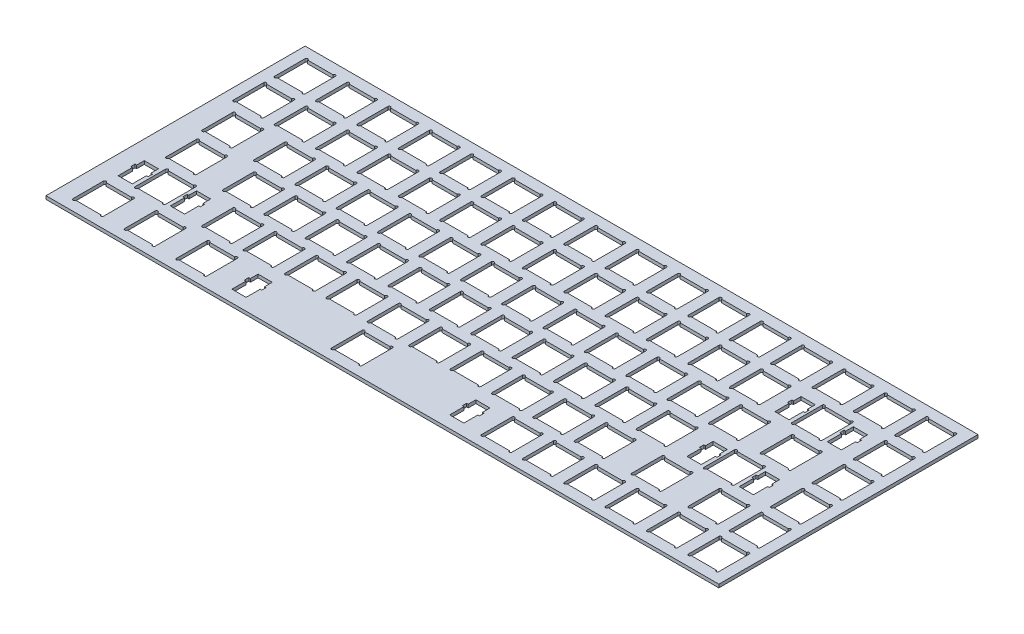
SolidWorks part; units mm, degrees
ref_plane "Спереди" through (0, 0, 0) normal (0, 0, 1) x (1, 0, 0)
ref_plane "Сверху" through (0, 0, 0) normal (0, 1, 0) x (1, 0, 0)
ref_plane "Справа" through (0, 0, 0) normal (1, 0, 0) x (0, 0, -1)
sketch "Эскиз1" plane through (0, 0, 0) normal (0, 1, 0) x (1, 0, 0)
  line L0 (13.2, -7) -> (24.8, -7)
  line L1 (-7, 7) -> (-7, -7)
  line L2 (-5.8, -7) -> (5.8, -7)
  line L3 (7, -7) -> (7, 7)
  line L4 (5.8, 7) -> (-5.8, 7)
  line L5 (12, 7) -> (12, -7)
  line L6 (24.8, 7) -> (13.2, 7)
  line L7 (26, -7) -> (26, 7)
  line L8 (32.2, -7) -> (43.8, -7)
  line L9 (31, 7) -> (31, -7)
  line L10 (43.8, 7) -> (32.2, 7)
  line L11 (45, -7) -> (45, 7)
  line L12 (51.2, -7) -> (62.8, -7)
  line L13 (50, 7) -> (50, -7)
  line L14 (62.8, 7) -> (51.2, 7)
  line L15 (64, -7) -> (64, 7)
  line L16 (70.2, -7) -> (81.8, -7)
  line L17 (69, 7) -> (69, -7)
  line L18 (81.8, 7) -> (70.2, 7)
  line L19 (83, -7) -> (83, 7)
  line L20 (89.2, -7) -> (100.8, -7)
  line L21 (88, 7) -> (88, -7)
  line L22 (100.8, 7) -> (89.2, 7)
  line L23 (102, -7) -> (102, 7)
  line L24 (108.2, -7) -> (119.8, -7)
  line L25 (107, 7) -> (107, -7)
  line L26 (119.8, 7) -> (108.2, 7)
  line L27 (121, -7) -> (121, 7)
  line L28 (127.2, -7) -> (138.8, -7)
  line L29 (126, 7) -> (126, -7)
  line L30 (138.8, 7) -> (127.2, 7)
  line L31 (140, -7) -> (140, 7)
  line L32 (146.2, -7) -> (157.8, -7)
  line L33 (145, 7) -> (145, -7)
  line L34 (157.8, 7) -> (146.2, 7)
  line L35 (159, -7) -> (159, 7)
  line L36 (165.2, -7) -> (176.8, -7)
  line L37 (164, 7) -> (164, -7)
  line L38 (176.8, 7) -> (165.2, 7)
  line L39 (178, -7) -> (178, 7)
  line L40 (184.2, -7) -> (195.8, -7)
  line L41 (183, 7) -> (183, -7)
  line L42 (195.8, 7) -> (184.2, 7)
  line L43 (197, -7) -> (197, 7)
  line L44 (203.2, -7) -> (214.8, -7)
  line L45 (202, 7) -> (202, -7)
  line L46 (214.8, 7) -> (203.2, 7)
  line L47 (216, -7) -> (216, 7)
  line L48 (222.2, -7) -> (233.8, -7)
  line L49 (221, 7) -> (221, -7)
  line L50 (233.8, 7) -> (222.2, 7)
  line L51 (235, -7) -> (235, 7)
  line L52 (241.2, -7) -> (252.8, -7)
  line L53 (240, 7) -> (240, -7)
  line L54 (252.8, 7) -> (241.2, 7)
  line L55 (254, -7) -> (254, 7)
  line L56 (260.2, -7) -> (271.8, -7)
  line L57 (259, 7) -> (259, -7)
  line L58 (271.8, 7) -> (260.2, 7)
  line L59 (273, -7) -> (273, 7)
  line L60 (279.2, -7) -> (290.8, -7)
  line L61 (278, 7) -> (278, -7)
  line L62 (290.8, 7) -> (279.2, 7)
  line L63 (292, -7) -> (292, 7)
  line L64 (279.2, -26) -> (290.8, -26)
  line L65 (278, -12) -> (278, -26)
  line L66 (290.8, -12) -> (279.2, -12)
  line L67 (292, -26) -> (292, -12)
  line L68 (279.2, -45) -> (290.8, -45)
  line L69 (278, -31) -> (278, -45)
  line L70 (290.8, -31) -> (279.2, -31)
  line L71 (292, -45) -> (292, -31)
  line L72 (279.2, -64) -> (290.8, -64)
  line L73 (278, -50) -> (278, -64)
  line L74 (290.8, -50) -> (279.2, -50)
  line L75 (292, -64) -> (292, -50)
  line L76 (279.2, -83) -> (290.8, -83)
  line L77 (278, -69) -> (278, -83)
  line L78 (290.8, -69) -> (279.2, -69)
  line L79 (292, -83) -> (292, -69)
  line L80 (279.2, -102) -> (290.8, -102)
  line L81 (278, -88) -> (278, -102)
  line L82 (290.8, -88) -> (279.2, -88)
  line L83 (292, -102) -> (292, -88)
  line L84 (-7, -12) -> (-7, -26)
  line L85 (-5.8, -26) -> (5.8, -26)
  line L86 (7, -26) -> (7, -12)
  line L87 (5.8, -12) -> (-5.8, -12)
  line L88 (12, -12) -> (12, -26)
  line L89 (13.2, -26) -> (24.8, -26)
  line L90 (26, -26) -> (26, -12)
  line L91 (24.8, -12) -> (13.2, -12)
  line L92 (31, -12) -> (31, -26)
  line L93 (32.2, -26) -> (43.8, -26)
  line L94 (45, -26) -> (45, -12)
  line L95 (43.8, -12) -> (32.2, -12)
  line L96 (50, -12) -> (50, -26)
  line L97 (51.2, -26) -> (62.8, -26)
  line L98 (64, -26) -> (64, -12)
  line L99 (62.8, -12) -> (51.2, -12)
  line L100 (69, -12) -> (69, -26)
  line L101 (70.2, -26) -> (81.8, -26)
  line L102 (83, -26) -> (83, -12)
  line L103 (81.8, -12) -> (70.2, -12)
  line L104 (88, -12) -> (88, -26)
  line L105 (89.2, -26) -> (100.8, -26)
  line L106 (102, -26) -> (102, -12)
  line L107 (100.8, -12) -> (89.2, -12)
  line L108 (107, -12) -> (107, -26)
  line L109 (108.2, -26) -> (119.8, -26)
  line L110 (121, -26) -> (121, -12)
  line L111 (119.8, -12) -> (108.2, -12)
  line L112 (126, -12) -> (126, -26)
  line L113 (127.2, -26) -> (138.8, -26)
  line L114 (140, -26) -> (140, -12)
  line L115 (138.8, -12) -> (127.2, -12)
  line L116 (145, -12) -> (145, -26)
  line L117 (146.2, -26) -> (157.8, -26)
  line L118 (159, -26) -> (159, -12)
  line L119 (157.8, -12) -> (146.2, -12)
  line L120 (164, -12) -> (164, -26)
  line L121 (165.2, -26) -> (176.8, -26)
  line L122 (178, -26) -> (178, -12)
  line L123 (176.8, -12) -> (165.2, -12)
  line L124 (183, -12) -> (183, -26)
  line L125 (184.2, -26) -> (195.8, -26)
  line L126 (197, -26) -> (197, -12)
  line L127 (195.8, -12) -> (184.2, -12)
  line L128 (202, -12) -> (202, -26)
  line L129 (203.2, -26) -> (214.8, -26)
  line L130 (216, -26) -> (216, -12)
  line L131 (214.8, -12) -> (203.2, -12)
  line L132 (221, -12) -> (221, -26)
  line L133 (222.2, -26) -> (233.8, -26)
  line L134 (235, -26) -> (235, -12)
  line L135 (233.8, -12) -> (222.2, -12)
  line L136 (260.2, -102) -> (271.8, -102)
  line L137 (259, -88) -> (259, -102)
  line L138 (271.8, -88) -> (260.2, -88)
  line L139 (273, -102) -> (273, -88)
  line L140 (241.2, -102) -> (252.8, -102)
  line L141 (240, -88) -> (240, -102)
  line L142 (252.8, -88) -> (241.2, -88)
  line L143 (254, -102) -> (254, -88)
  line L144 (222.2, -102) -> (233.8, -102)
  line L145 (221, -88) -> (221, -102)
  line L146 (233.8, -88) -> (222.2, -88)
  line L147 (235, -102) -> (235, -88)
  line L148 (203.2, -102) -> (214.8, -102)
  line L149 (202, -88) -> (202, -102)
  line L150 (214.8, -88) -> (203.2, -88)
  line L151 (216, -102) -> (216, -88)
  line L152 (184.2, -102) -> (195.8, -102)
  line L153 (183, -88) -> (183, -102)
  line L154 (195.8, -88) -> (184.2, -88)
  line L155 (197, -102) -> (197, -88)
  line L156 (263.5, -26) -> (263.5, -12)
  line L157 (-12, 12) -> (297, 12)
  line L158 (-12, 12) -> (-12, -107)
  line L159 (-12, -107) -> (297, -107)
  line L160 (297, 12) -> (297, -107)
  line L161 (262.3, -12) -> (250.7, -12)
  line L162 (250.7, -26) -> (262.3, -26)
  line L163 (249.5, -12) -> (249.5, -26)
  line L164 (11.75, -45) -> (11.75, -31)
  line L169 (-2.25, -31) -> (-2.25, -45)
  line L170 (-1.05, -45) -> (10.55, -45)
  line L171 (10.55, -31) -> (-1.05, -31)
  line L172 (35.5, -45) -> (35.5, -31)
  line L173 (21.5, -31) -> (21.5, -45)
  line L174 (22.7, -45) -> (34.3, -45)
  line L175 (34.3, -31) -> (22.7, -31)
  line L176 (54.5, -45) -> (54.5, -31)
  line L177 (40.5, -31) -> (40.5, -45)
  line L178 (41.7, -45) -> (53.3, -45)
  line L179 (53.3, -31) -> (41.7, -31)
  line L180 (73.5, -45) -> (73.5, -31)
  line L181 (59.5, -31) -> (59.5, -45)
  line L182 (60.7, -45) -> (72.3, -45)
  line L183 (72.3, -31) -> (60.7, -31)
  line L184 (92.5, -45) -> (92.5, -31)
  line L185 (78.5, -31) -> (78.5, -45)
  line L186 (79.7, -45) -> (91.3, -45)
  line L187 (91.3, -31) -> (79.7, -31)
  line L188 (111.5, -45) -> (111.5, -31)
  line L189 (97.5, -31) -> (97.5, -45)
  line L190 (98.7, -45) -> (110.3, -45)
  line L191 (110.3, -31) -> (98.7, -31)
  line L192 (130.5, -45) -> (130.5, -31)
  line L193 (116.5, -31) -> (116.5, -45)
  line L194 (117.7, -45) -> (129.3, -45)
  line L195 (129.3, -31) -> (117.7, -31)
  line L196 (149.5, -45) -> (149.5, -31)
  line L197 (135.5, -31) -> (135.5, -45)
  line L198 (136.7, -45) -> (148.3, -45)
  line L199 (148.3, -31) -> (136.7, -31)
  line L200 (168.5, -45) -> (168.5, -31)
  line L201 (154.5, -31) -> (154.5, -45)
  line L202 (155.7, -45) -> (167.3, -45)
  line L203 (167.3, -31) -> (155.7, -31)
  line L204 (187.5, -45) -> (187.5, -31)
  line L205 (173.5, -31) -> (173.5, -45)
  line L206 (174.7, -45) -> (186.3, -45)
  line L207 (186.3, -31) -> (174.7, -31)
  line L208 (206.5, -45) -> (206.5, -31)
  line L209 (192.5, -31) -> (192.5, -45)
  line L210 (193.7, -45) -> (205.3, -45)
  line L211 (205.3, -31) -> (193.7, -31)
  line L212 (225.5, -45) -> (225.5, -31)
  line L213 (211.5, -31) -> (211.5, -45)
  line L214 (212.7, -45) -> (224.3, -45)
  line L215 (224.3, -31) -> (212.7, -31)
  line L216 (244.5, -45) -> (244.5, -31)
  line L217 (230.5, -31) -> (230.5, -45)
  line L218 (231.7, -45) -> (243.3, -45)
  line L219 (243.3, -31) -> (231.7, -31)
  line L220 (268.25, -45) -> (268.25, -31)
  line L221 (254.25, -31) -> (254.25, -45)
  line L222 (255.45, -45) -> (267.05, -45)
  line L223 (267.05, -31) -> (255.45, -31)
  line L224 (14.125, -64) -> (14.125, -50)
  line L225 (0.125, -50) -> (0.125, -64)
  line L226 (1.325, -64) -> (12.925, -64)
  line L227 (12.925, -50) -> (1.325, -50)
  line L228 (40.25, -64) -> (40.25, -50)
  line L229 (26.25, -50) -> (26.25, -64)
  line L230 (27.45, -64) -> (39.05, -64)
  line L231 (39.05, -50) -> (27.45, -50)
  line L232 (59.25, -64) -> (59.25, -50)
  line L233 (45.25, -50) -> (45.25, -64)
  line L234 (46.45, -64) -> (58.05, -64)
  line L235 (58.05, -50) -> (46.45, -50)
  line L236 (78.25, -64) -> (78.25, -50)
  line L237 (64.25, -50) -> (64.25, -64)
  line L238 (65.45, -64) -> (77.05, -64)
  line L239 (77.05, -50) -> (65.45, -50)
  line L240 (97.25, -64) -> (97.25, -50)
  line L241 (83.25, -50) -> (83.25, -64)
  line L242 (84.45, -64) -> (96.05, -64)
  line L243 (96.05, -50) -> (84.45, -50)
  line L244 (116.25, -64) -> (116.25, -50)
  line L245 (102.25, -50) -> (102.25, -64)
  line L246 (103.45, -64) -> (115.05, -64)
  line L247 (115.05, -50) -> (103.45, -50)
  line L248 (135.25, -64) -> (135.25, -50)
  line L249 (121.25, -50) -> (121.25, -64)
  line L250 (122.45, -64) -> (134.05, -64)
  line L251 (134.05, -50) -> (122.45, -50)
  line L252 (154.25, -64) -> (154.25, -50)
  line L253 (140.25, -50) -> (140.25, -64)
  line L254 (141.45, -64) -> (153.05, -64)
  line L255 (153.05, -50) -> (141.45, -50)
  line L256 (173.25, -64) -> (173.25, -50)
  line L257 (159.25, -50) -> (159.25, -64)
  line L258 (160.45, -64) -> (172.05, -64)
  line L259 (172.05, -50) -> (160.45, -50)
  line L260 (192.25, -64) -> (192.25, -50)
  line L261 (178.25, -50) -> (178.25, -64)
  line L262 (179.45, -64) -> (191.05, -64)
  line L263 (191.05, -50) -> (179.45, -50)
  line L264 (211.25, -64) -> (211.25, -50)
  line L265 (197.25, -50) -> (197.25, -64)
  line L266 (198.45, -64) -> (210.05, -64)
  line L267 (210.05, -50) -> (198.45, -50)
  line L268 (230.25, -64) -> (230.25, -50)
  line L269 (216.25, -50) -> (216.25, -64)
  line L270 (217.45, -64) -> (229.05, -64)
  line L271 (229.05, -50) -> (217.45, -50)
  line L272 (261.125, -64) -> (261.125, -50)
  line L273 (247.125, -50) -> (247.125, -64)
  line L274 (248.325, -64) -> (259.925, -64)
  line L275 (259.925, -50) -> (248.325, -50)
  line L276 (273, -83) -> (273, -69)
  line L277 (259, -69) -> (259, -83)
  line L278 (260.2, -83) -> (271.8, -83)
  line L279 (271.8, -69) -> (260.2, -69)
  line L280 (246.875, -83) -> (246.875, -69)
  line L281 (232.875, -69) -> (232.875, -83)
  line L282 (234.075, -83) -> (245.675, -83)
  line L283 (245.675, -69) -> (234.075, -69)
  line L284 (220.75, -83) -> (220.75, -69)
  line L285 (206.75, -69) -> (206.75, -83)
  line L286 (207.95, -83) -> (219.55, -83)
  line L287 (219.55, -69) -> (207.95, -69)
  line L288 (201.75, -83) -> (201.75, -69)
  line L289 (187.75, -69) -> (187.75, -83)
  line L290 (188.95, -83) -> (200.55, -83)
  line L291 (200.55, -69) -> (188.95, -69)
  line L292 (182.75, -83) -> (182.75, -69)
  line L293 (168.75, -69) -> (168.75, -83)
  line L294 (169.95, -83) -> (181.55, -83)
  line L295 (181.55, -69) -> (169.95, -69)
  line L296 (163.75, -83) -> (163.75, -69)
  line L297 (149.75, -69) -> (149.75, -83)
  line L298 (150.95, -83) -> (162.55, -83)
  line L299 (162.55, -69) -> (150.95, -69)
  line L300 (144.75, -83) -> (144.75, -69)
  line L301 (130.75, -69) -> (130.75, -83)
  line L302 (131.95, -83) -> (143.55, -83)
  line L303 (143.55, -69) -> (131.95, -69)
  line L304 (125.75, -83) -> (125.75, -69)
  line L305 (111.75, -69) -> (111.75, -83)
  line L306 (112.95, -83) -> (124.55, -83)
  line L307 (124.55, -69) -> (112.95, -69)
  line L308 (106.75, -83) -> (106.75, -69)
  line L309 (92.75, -69) -> (92.75, -83)
  line L310 (93.95, -83) -> (105.55, -83)
  line L311 (105.55, -69) -> (93.95, -69)
  line L312 (87.75, -83) -> (87.75, -69)
  line L313 (73.75, -69) -> (73.75, -83)
  line L314 (74.95, -83) -> (86.55, -83)
  line L315 (86.55, -69) -> (74.95, -69)
  line L316 (68.75, -83) -> (68.75, -69)
  line L317 (54.75, -69) -> (54.75, -83)
  line L318 (55.95, -83) -> (67.55, -83)
  line L319 (67.55, -69) -> (55.95, -69)
  line L320 (49.75, -83) -> (49.75, -69)
  line L321 (35.75, -69) -> (35.75, -83)
  line L322 (36.95, -83) -> (48.55, -83)
  line L323 (48.55, -69) -> (36.95, -69)
  line L324 (18.875, -83) -> (18.875, -69)
  line L325 (4.875, -69) -> (4.875, -83)
  line L326 (6.075, -83) -> (17.675, -83)
  line L327 (17.675, -69) -> (6.075, -69)
  line L328 (9.375, -102) -> (9.375, -88)
  line L329 (-4.625, -88) -> (-4.625, -102)
  line L330 (-3.425, -102) -> (8.175, -102)
  line L331 (8.175, -88) -> (-3.425, -88)
  line L332 (33.125, -102) -> (33.125, -88)
  line L333 (19.125, -88) -> (19.125, -102)
  line L334 (20.325, -102) -> (31.925, -102)
  line L335 (31.925, -88) -> (20.325, -88)
  line L336 (56.875, -102) -> (56.875, -88)
  line L337 (42.875, -88) -> (42.875, -102)
  line L338 (44.075, -102) -> (55.675, -102)
  line L339 (55.675, -88) -> (44.075, -88)
  line L340 (128.125, -102) -> (128.125, -88)
  line L341 (114.125, -88) -> (114.125, -102)
  line L342 (115.325, -102) -> (126.925, -102)
  line L343 (126.925, -88) -> (115.325, -88)
  line L356 (67.125, -95) -> (67.875, -95)
  line L357 (75.125, -93) -> (74.375, -93)
  line L358 (67.875, -101.5) -> (74.375, -101.5)
  line L359 (74.375, -95) -> (75.125, -95)
  line L360 (67.875, -89.5) -> (74.375, -89.5)
  line L361 (74.375, -101.5) -> (74.375, -95)
  line L362 (67.125, -93) -> (67.125, -95)
  line L363 (67.875, -93) -> (67.125, -93)
  line L364 (74.375, -93) -> (74.375, -89.5)
  line L365 (67.875, -93) -> (67.875, -89.5)
  line L366 (67.875, -101.5) -> (67.875, -95)
  line L367 (75.125, -95) -> (75.125, -93)
  line L368 (167.125, -95) -> (167.875, -95)
  line L369 (175.125, -93) -> (174.375, -93)
  line L370 (167.875, -101.5) -> (174.375, -101.5)
  line L371 (174.375, -95) -> (175.125, -95)
  line L372 (167.875, -89.5) -> (174.375, -89.5)
  line L373 (174.375, -101.5) -> (174.375, -95)
  line L374 (167.125, -93) -> (167.125, -95)
  line L375 (167.875, -93) -> (167.125, -93)
  line L376 (174.375, -93) -> (174.375, -89.5)
  line L377 (167.875, -93) -> (167.875, -89.5)
  line L378 (167.875, -101.5) -> (167.875, -95)
  line L379 (175.125, -95) -> (175.125, -93)
  line L380 (19.875, -76) -> (20.625, -76)
  line L381 (27.875, -74) -> (27.125, -74)
  line L382 (20.625, -82.5) -> (27.125, -82.5)
  line L383 (27.125, -76) -> (27.875, -76)
  line L384 (20.625, -70.5) -> (27.125, -70.5)
  line L385 (27.125, -82.5) -> (27.125, -76)
  line L386 (19.875, -74) -> (19.875, -76)
  line L387 (20.625, -74) -> (19.875, -74)
  line L388 (27.125, -74) -> (27.125, -70.5)
  line L389 (20.625, -74) -> (20.625, -70.5)
  line L390 (20.625, -82.5) -> (20.625, -76)
  line L391 (27.875, -76) -> (27.875, -74)
  line L392 (-4.125, -76) -> (-3.375, -76)
  line L393 (3.875, -74) -> (3.125, -74)
  line L394 (-3.375, -82.5) -> (3.125, -82.5)
  line L395 (3.125, -76) -> (3.875, -76)
  line L396 (-3.375, -70.5) -> (3.125, -70.5)
  line L397 (3.125, -82.5) -> (3.125, -76)
  line L398 (-4.125, -74) -> (-4.125, -76)
  line L399 (-3.375, -74) -> (-4.125, -74)
  line L400 (3.125, -74) -> (3.125, -70.5)
  line L401 (-3.375, -74) -> (-3.375, -70.5)
  line L402 (-3.375, -82.5) -> (-3.375, -76)
  line L403 (3.875, -76) -> (3.875, -74)
  line L404 (238.125, -57) -> (238.875, -57)
  line L405 (246.125, -55) -> (245.375, -55)
  line L406 (238.875, -63.5) -> (245.375, -63.5)
  line L407 (245.375, -57) -> (246.125, -57)
  line L408 (238.875, -51.5) -> (245.375, -51.5)
  line L409 (245.375, -63.5) -> (245.375, -57)
  line L410 (238.125, -55) -> (238.125, -57)
  line L411 (238.875, -55) -> (238.125, -55)
  line L412 (245.375, -55) -> (245.375, -51.5)
  line L413 (238.875, -55) -> (238.875, -51.5)
  line L414 (238.875, -63.5) -> (238.875, -57)
  line L415 (246.125, -57) -> (246.125, -55)
  line L416 (262.125, -57) -> (262.875, -57)
  line L417 (270.125, -55) -> (269.375, -55)
  line L418 (262.875, -63.5) -> (269.375, -63.5)
  line L419 (269.375, -57) -> (270.125, -57)
  line L420 (262.875, -51.5) -> (269.375, -51.5)
  line L421 (269.375, -63.5) -> (269.375, -57)
  line L422 (262.125, -55) -> (262.125, -57)
  line L423 (262.875, -55) -> (262.125, -55)
  line L424 (269.375, -55) -> (269.375, -51.5)
  line L425 (262.875, -55) -> (262.875, -51.5)
  line L426 (262.875, -63.5) -> (262.875, -57)
  line L427 (270.125, -57) -> (270.125, -55)
  line L428 (240.5, -19) -> (241.25, -19)
  line L429 (248.5, -17) -> (247.75, -17)
  line L430 (241.25, -25.5) -> (247.75, -25.5)
  line L431 (247.75, -19) -> (248.5, -19)
  line L432 (241.25, -13.5) -> (247.75, -13.5)
  line L433 (247.75, -25.5) -> (247.75, -19)
  line L434 (240.5, -17) -> (240.5, -19)
  line L435 (241.25, -17) -> (240.5, -17)
  line L436 (247.75, -17) -> (247.75, -13.5)
  line L437 (241.25, -17) -> (241.25, -13.5)
  line L438 (241.25, -25.5) -> (241.25, -19)
  line L439 (248.5, -19) -> (248.5, -17)
  line L440 (264.5, -19) -> (265.25, -19)
  line L441 (272.5, -17) -> (271.75, -17)
  line L442 (265.25, -25.5) -> (271.75, -25.5)
  line L443 (271.75, -19) -> (272.5, -19)
  line L444 (265.25, -13.5) -> (271.75, -13.5)
  line L445 (271.75, -25.5) -> (271.75, -19)
  line L446 (264.5, -17) -> (264.5, -19)
  line L447 (265.25, -17) -> (264.5, -17)
  line L448 (271.75, -17) -> (271.75, -13.5)
  line L449 (265.25, -17) -> (265.25, -13.5)
  line L450 (265.25, -25.5) -> (265.25, -19)
  line L451 (272.5, -19) -> (272.5, -17)
  arc A0 (-7, 7) -> (-5.8, 7) centre (-6.4, 7) cw
  arc A1 (5.8, 7) -> (7, 7) centre (6.4, 7) cw
  arc A2 (-7, -7) -> (-5.8, -7) centre (-6.4, -7) ccw
  arc A3 (5.8, -7) -> (7, -7) centre (6.4, -7) ccw
  arc A4 (24.8, -7) -> (26, -7) centre (25.4, -7) ccw
  arc A5 (12, -7) -> (13.2, -7) centre (12.6, -7) ccw
  arc A6 (12, 7) -> (13.2, 7) centre (12.6, 7) cw
  arc A7 (24.8, 7) -> (26, 7) centre (25.4, 7) cw
  arc A8 (43.8, -7) -> (45, -7) centre (44.4, -7) ccw
  arc A9 (31, -7) -> (32.2, -7) centre (31.6, -7) ccw
  arc A10 (31, 7) -> (32.2, 7) centre (31.6, 7) cw
  arc A11 (43.8, 7) -> (45, 7) centre (44.4, 7) cw
  arc A12 (62.8, -7) -> (64, -7) centre (63.4, -7) ccw
  arc A13 (50, -7) -> (51.2, -7) centre (50.6, -7) ccw
  arc A14 (50, 7) -> (51.2, 7) centre (50.6, 7) cw
  arc A15 (62.8, 7) -> (64, 7) centre (63.4, 7) cw
  arc A16 (81.8, -7) -> (83, -7) centre (82.4, -7) ccw
  arc A17 (69, -7) -> (70.2, -7) centre (69.6, -7) ccw
  arc A18 (69, 7) -> (70.2, 7) centre (69.6, 7) cw
  arc A19 (81.8, 7) -> (83, 7) centre (82.4, 7) cw
  arc A20 (100.8, -7) -> (102, -7) centre (101.4, -7) ccw
  arc A21 (88, -7) -> (89.2, -7) centre (88.6, -7) ccw
  arc A22 (88, 7) -> (89.2, 7) centre (88.6, 7) cw
  arc A23 (100.8, 7) -> (102, 7) centre (101.4, 7) cw
  arc A24 (119.8, -7) -> (121, -7) centre (120.4, -7) ccw
  arc A25 (107, -7) -> (108.2, -7) centre (107.6, -7) ccw
  arc A26 (107, 7) -> (108.2, 7) centre (107.6, 7) cw
  arc A27 (119.8, 7) -> (121, 7) centre (120.4, 7) cw
  arc A28 (138.8, -7) -> (140, -7) centre (139.4, -7) ccw
  arc A29 (126, -7) -> (127.2, -7) centre (126.6, -7) ccw
  arc A30 (126, 7) -> (127.2, 7) centre (126.6, 7) cw
  arc A31 (138.8, 7) -> (140, 7) centre (139.4, 7) cw
  arc A32 (157.8, -7) -> (159, -7) centre (158.4, -7) ccw
  arc A33 (145, -7) -> (146.2, -7) centre (145.6, -7) ccw
  arc A34 (145, 7) -> (146.2, 7) centre (145.6, 7) cw
  arc A35 (157.8, 7) -> (159, 7) centre (158.4, 7) cw
  arc A36 (176.8, -7) -> (178, -7) centre (177.4, -7) ccw
  arc A37 (164, -7) -> (165.2, -7) centre (164.6, -7) ccw
  arc A38 (164, 7) -> (165.2, 7) centre (164.6, 7) cw
  arc A39 (176.8, 7) -> (178, 7) centre (177.4, 7) cw
  arc A40 (195.8, -7) -> (197, -7) centre (196.4, -7) ccw
  arc A41 (183, -7) -> (184.2, -7) centre (183.6, -7) ccw
  arc A42 (183, 7) -> (184.2, 7) centre (183.6, 7) cw
  arc A43 (195.8, 7) -> (197, 7) centre (196.4, 7) cw
  arc A44 (214.8, -7) -> (216, -7) centre (215.4, -7) ccw
  arc A45 (202, -7) -> (203.2, -7) centre (202.6, -7) ccw
  arc A46 (202, 7) -> (203.2, 7) centre (202.6, 7) cw
  arc A47 (214.8, 7) -> (216, 7) centre (215.4, 7) cw
  arc A48 (233.8, -7) -> (235, -7) centre (234.4, -7) ccw
  arc A49 (221, -7) -> (222.2, -7) centre (221.6, -7) ccw
  arc A50 (221, 7) -> (222.2, 7) centre (221.6, 7) cw
  arc A51 (233.8, 7) -> (235, 7) centre (234.4, 7) cw
  arc A52 (252.8, -7) -> (254, -7) centre (253.4, -7) ccw
  arc A53 (240, -7) -> (241.2, -7) centre (240.6, -7) ccw
  arc A54 (240, 7) -> (241.2, 7) centre (240.6, 7) cw
  arc A55 (252.8, 7) -> (254, 7) centre (253.4, 7) cw
  arc A56 (271.8, -7) -> (273, -7) centre (272.4, -7) ccw
  arc A57 (259, -7) -> (260.2, -7) centre (259.6, -7) ccw
  arc A58 (259, 7) -> (260.2, 7) centre (259.6, 7) cw
  arc A59 (271.8, 7) -> (273, 7) centre (272.4, 7) cw
  arc A60 (290.8, -7) -> (292, -7) centre (291.4, -7) ccw
  arc A61 (278, -7) -> (279.2, -7) centre (278.6, -7) ccw
  arc A62 (278, 7) -> (279.2, 7) centre (278.6, 7) cw
  arc A63 (290.8, 7) -> (292, 7) centre (291.4, 7) cw
  arc A64 (290.8, -26) -> (292, -26) centre (291.4, -26) ccw
  arc A65 (278, -26) -> (279.2, -26) centre (278.6, -26) ccw
  arc A66 (278, -12) -> (279.2, -12) centre (278.6, -12) cw
  arc A67 (290.8, -12) -> (292, -12) centre (291.4, -12) cw
  arc A68 (290.8, -45) -> (292, -45) centre (291.4, -45) ccw
  arc A69 (278, -45) -> (279.2, -45) centre (278.6, -45) ccw
  arc A70 (278, -31) -> (279.2, -31) centre (278.6, -31) cw
  arc A71 (290.8, -31) -> (292, -31) centre (291.4, -31) cw
  arc A72 (290.8, -64) -> (292, -64) centre (291.4, -64) ccw
  arc A73 (278, -64) -> (279.2, -64) centre (278.6, -64) ccw
  arc A74 (278, -50) -> (279.2, -50) centre (278.6, -50) cw
  arc A75 (290.8, -50) -> (292, -50) centre (291.4, -50) cw
  arc A76 (290.8, -83) -> (292, -83) centre (291.4, -83) ccw
  arc A77 (278, -83) -> (279.2, -83) centre (278.6, -83) ccw
  arc A78 (278, -69) -> (279.2, -69) centre (278.6, -69) cw
  arc A79 (290.8, -69) -> (292, -69) centre (291.4, -69) cw
  arc A80 (290.8, -102) -> (292, -102) centre (291.4, -102) ccw
  arc A81 (278, -102) -> (279.2, -102) centre (278.6, -102) ccw
  arc A82 (278, -88) -> (279.2, -88) centre (278.6, -88) cw
  arc A83 (290.8, -88) -> (292, -88) centre (291.4, -88) cw
  arc A84 (-7, -12) -> (-5.8, -12) centre (-6.4, -12) cw
  arc A85 (5.8, -12) -> (7, -12) centre (6.4, -12) cw
  arc A86 (-7, -26) -> (-5.8, -26) centre (-6.4, -26) ccw
  arc A87 (5.8, -26) -> (7, -26) centre (6.4, -26) ccw
  arc A88 (12, -12) -> (13.2, -12) centre (12.6, -12) cw
  arc A89 (24.8, -12) -> (26, -12) centre (25.4, -12) cw
  arc A90 (12, -26) -> (13.2, -26) centre (12.6, -26) ccw
  arc A91 (24.8, -26) -> (26, -26) centre (25.4, -26) ccw
  arc A92 (31, -12) -> (32.2, -12) centre (31.6, -12) cw
  arc A93 (43.8, -12) -> (45, -12) centre (44.4, -12) cw
  arc A94 (31, -26) -> (32.2, -26) centre (31.6, -26) ccw
  arc A95 (43.8, -26) -> (45, -26) centre (44.4, -26) ccw
  arc A96 (50, -12) -> (51.2, -12) centre (50.6, -12) cw
  arc A97 (62.8, -12) -> (64, -12) centre (63.4, -12) cw
  arc A98 (50, -26) -> (51.2, -26) centre (50.6, -26) ccw
  arc A99 (62.8, -26) -> (64, -26) centre (63.4, -26) ccw
  arc A100 (69, -12) -> (70.2, -12) centre (69.6, -12) cw
  arc A101 (81.8, -12) -> (83, -12) centre (82.4, -12) cw
  arc A102 (69, -26) -> (70.2, -26) centre (69.6, -26) ccw
  arc A103 (81.8, -26) -> (83, -26) centre (82.4, -26) ccw
  arc A104 (88, -12) -> (89.2, -12) centre (88.6, -12) cw
  arc A105 (100.8, -12) -> (102, -12) centre (101.4, -12) cw
  arc A106 (88, -26) -> (89.2, -26) centre (88.6, -26) ccw
  arc A107 (100.8, -26) -> (102, -26) centre (101.4, -26) ccw
  arc A108 (107, -12) -> (108.2, -12) centre (107.6, -12) cw
  arc A109 (119.8, -12) -> (121, -12) centre (120.4, -12) cw
  arc A110 (107, -26) -> (108.2, -26) centre (107.6, -26) ccw
  arc A111 (119.8, -26) -> (121, -26) centre (120.4, -26) ccw
  arc A112 (126, -12) -> (127.2, -12) centre (126.6, -12) cw
  arc A113 (138.8, -12) -> (140, -12) centre (139.4, -12) cw
  arc A114 (126, -26) -> (127.2, -26) centre (126.6, -26) ccw
  arc A115 (138.8, -26) -> (140, -26) centre (139.4, -26) ccw
  arc A116 (145, -12) -> (146.2, -12) centre (145.6, -12) cw
  arc A117 (157.8, -12) -> (159, -12) centre (158.4, -12) cw
  arc A118 (145, -26) -> (146.2, -26) centre (145.6, -26) ccw
  arc A119 (157.8, -26) -> (159, -26) centre (158.4, -26) ccw
  arc A120 (164, -12) -> (165.2, -12) centre (164.6, -12) cw
  arc A121 (176.8, -12) -> (178, -12) centre (177.4, -12) cw
  arc A122 (164, -26) -> (165.2, -26) centre (164.6, -26) ccw
  arc A123 (176.8, -26) -> (178, -26) centre (177.4, -26) ccw
  arc A124 (183, -12) -> (184.2, -12) centre (183.6, -12) cw
  arc A125 (195.8, -12) -> (197, -12) centre (196.4, -12) cw
  arc A126 (183, -26) -> (184.2, -26) centre (183.6, -26) ccw
  arc A127 (195.8, -26) -> (197, -26) centre (196.4, -26) ccw
  arc A128 (202, -12) -> (203.2, -12) centre (202.6, -12) cw
  arc A129 (214.8, -12) -> (216, -12) centre (215.4, -12) cw
  arc A130 (202, -26) -> (203.2, -26) centre (202.6, -26) ccw
  arc A131 (214.8, -26) -> (216, -26) centre (215.4, -26) ccw
  arc A132 (221, -12) -> (222.2, -12) centre (221.6, -12) cw
  arc A133 (233.8, -12) -> (235, -12) centre (234.4, -12) cw
  arc A134 (221, -26) -> (222.2, -26) centre (221.6, -26) ccw
  arc A135 (233.8, -26) -> (235, -26) centre (234.4, -26) ccw
  arc A136 (271.8, -102) -> (273, -102) centre (272.4, -102) ccw
  arc A137 (259, -102) -> (260.2, -102) centre (259.6, -102) ccw
  arc A138 (259, -88) -> (260.2, -88) centre (259.6, -88) cw
  arc A139 (271.8, -88) -> (273, -88) centre (272.4, -88) cw
  arc A140 (252.8, -102) -> (254, -102) centre (253.4, -102) ccw
  arc A141 (240, -102) -> (241.2, -102) centre (240.6, -102) ccw
  arc A142 (240, -88) -> (241.2, -88) centre (240.6, -88) cw
  arc A143 (252.8, -88) -> (254, -88) centre (253.4, -88) cw
  arc A144 (233.8, -102) -> (235, -102) centre (234.4, -102) ccw
  arc A145 (221, -102) -> (222.2, -102) centre (221.6, -102) ccw
  arc A146 (221, -88) -> (222.2, -88) centre (221.6, -88) cw
  arc A147 (233.8, -88) -> (235, -88) centre (234.4, -88) cw
  arc A148 (214.8, -102) -> (216, -102) centre (215.4, -102) ccw
  arc A149 (202, -102) -> (203.2, -102) centre (202.6, -102) ccw
  arc A150 (202, -88) -> (203.2, -88) centre (202.6, -88) cw
  arc A151 (214.8, -88) -> (216, -88) centre (215.4, -88) cw
  arc A152 (195.8, -102) -> (197, -102) centre (196.4, -102) ccw
  arc A153 (183, -102) -> (184.2, -102) centre (183.6, -102) ccw
  arc A154 (183, -88) -> (184.2, -88) centre (183.6, -88) cw
  arc A155 (195.8, -88) -> (197, -88) centre (196.4, -88) cw
  arc A156 (262.3, -26) -> (263.5, -26) centre (262.9, -26) ccw
  arc A157 (249.5, -26) -> (250.7, -26) centre (250.1, -26) ccw
  arc A158 (249.5, -12) -> (250.7, -12) centre (250.1, -12) cw
  arc A159 (262.3, -12) -> (263.5, -12) centre (262.9, -12) cw
  arc A160 (-2.25, -45) -> (-1.05, -45) centre (-1.65, -45) ccw
  arc A161 (-2.25, -31) -> (-1.05, -31) centre (-1.65, -31) cw
  arc A162 (10.55, -45) -> (11.75, -45) centre (11.15, -45) ccw
  arc A163 (10.55, -31) -> (11.75, -31) centre (11.15, -31) cw
  arc A164 (21.5, -45) -> (22.7, -45) centre (22.1, -45) ccw
  arc A165 (21.5, -31) -> (22.7, -31) centre (22.1, -31) cw
  arc A166 (34.3, -45) -> (35.5, -45) centre (34.9, -45) ccw
  arc A167 (34.3, -31) -> (35.5, -31) centre (34.9, -31) cw
  arc A168 (40.5, -45) -> (41.7, -45) centre (41.1, -45) ccw
  arc A169 (40.5, -31) -> (41.7, -31) centre (41.1, -31) cw
  arc A170 (53.3, -45) -> (54.5, -45) centre (53.9, -45) ccw
  arc A171 (53.3, -31) -> (54.5, -31) centre (53.9, -31) cw
  arc A172 (59.5, -45) -> (60.7, -45) centre (60.1, -45) ccw
  arc A173 (59.5, -31) -> (60.7, -31) centre (60.1, -31) cw
  arc A174 (72.3, -45) -> (73.5, -45) centre (72.9, -45) ccw
  arc A175 (72.3, -31) -> (73.5, -31) centre (72.9, -31) cw
  arc A176 (78.5, -45) -> (79.7, -45) centre (79.1, -45) ccw
  arc A177 (78.5, -31) -> (79.7, -31) centre (79.1, -31) cw
  arc A178 (91.3, -45) -> (92.5, -45) centre (91.9, -45) ccw
  arc A179 (91.3, -31) -> (92.5, -31) centre (91.9, -31) cw
  arc A180 (97.5, -45) -> (98.7, -45) centre (98.1, -45) ccw
  arc A181 (97.5, -31) -> (98.7, -31) centre (98.1, -31) cw
  arc A182 (110.3, -45) -> (111.5, -45) centre (110.9, -45) ccw
  arc A183 (110.3, -31) -> (111.5, -31) centre (110.9, -31) cw
  arc A184 (116.5, -45) -> (117.7, -45) centre (117.1, -45) ccw
  arc A185 (116.5, -31) -> (117.7, -31) centre (117.1, -31) cw
  arc A186 (129.3, -45) -> (130.5, -45) centre (129.9, -45) ccw
  arc A187 (129.3, -31) -> (130.5, -31) centre (129.9, -31) cw
  arc A188 (135.5, -45) -> (136.7, -45) centre (136.1, -45) ccw
  arc A189 (135.5, -31) -> (136.7, -31) centre (136.1, -31) cw
  arc A190 (148.3, -45) -> (149.5, -45) centre (148.9, -45) ccw
  arc A191 (148.3, -31) -> (149.5, -31) centre (148.9, -31) cw
  arc A192 (154.5, -45) -> (155.7, -45) centre (155.1, -45) ccw
  arc A193 (154.5, -31) -> (155.7, -31) centre (155.1, -31) cw
  arc A194 (167.3, -45) -> (168.5, -45) centre (167.9, -45) ccw
  arc A195 (167.3, -31) -> (168.5, -31) centre (167.9, -31) cw
  arc A196 (173.5, -45) -> (174.7, -45) centre (174.1, -45) ccw
  arc A197 (173.5, -31) -> (174.7, -31) centre (174.1, -31) cw
  arc A198 (186.3, -45) -> (187.5, -45) centre (186.9, -45) ccw
  arc A199 (186.3, -31) -> (187.5, -31) centre (186.9, -31) cw
  arc A200 (192.5, -45) -> (193.7, -45) centre (193.1, -45) ccw
  arc A201 (192.5, -31) -> (193.7, -31) centre (193.1, -31) cw
  arc A202 (205.3, -45) -> (206.5, -45) centre (205.9, -45) ccw
  arc A203 (205.3, -31) -> (206.5, -31) centre (205.9, -31) cw
  arc A204 (211.5, -45) -> (212.7, -45) centre (212.1, -45) ccw
  arc A205 (211.5, -31) -> (212.7, -31) centre (212.1, -31) cw
  arc A206 (224.3, -45) -> (225.5, -45) centre (224.9, -45) ccw
  arc A207 (224.3, -31) -> (225.5, -31) centre (224.9, -31) cw
  arc A208 (230.5, -45) -> (231.7, -45) centre (231.1, -45) ccw
  arc A209 (230.5, -31) -> (231.7, -31) centre (231.1, -31) cw
  arc A210 (243.3, -45) -> (244.5, -45) centre (243.9, -45) ccw
  arc A211 (243.3, -31) -> (244.5, -31) centre (243.9, -31) cw
  arc A212 (254.25, -45) -> (255.45, -45) centre (254.85, -45) ccw
  arc A213 (254.25, -31) -> (255.45, -31) centre (254.85, -31) cw
  arc A214 (267.05, -45) -> (268.25, -45) centre (267.65, -45) ccw
  arc A215 (267.05, -31) -> (268.25, -31) centre (267.65, -31) cw
  arc A216 (0.125, -64) -> (1.325, -64) centre (0.725, -64) ccw
  arc A217 (0.125, -50) -> (1.325, -50) centre (0.725, -50) cw
  arc A218 (12.925, -64) -> (14.125, -64) centre (13.525, -64) ccw
  arc A219 (12.925, -50) -> (14.125, -50) centre (13.525, -50) cw
  arc A220 (26.25, -64) -> (27.45, -64) centre (26.85, -64) ccw
  arc A221 (26.25, -50) -> (27.45, -50) centre (26.85, -50) cw
  arc A222 (39.05, -64) -> (40.25, -64) centre (39.65, -64) ccw
  arc A223 (39.05, -50) -> (40.25, -50) centre (39.65, -50) cw
  arc A224 (45.25, -64) -> (46.45, -64) centre (45.85, -64) ccw
  arc A225 (45.25, -50) -> (46.45, -50) centre (45.85, -50) cw
  arc A226 (58.05, -64) -> (59.25, -64) centre (58.65, -64) ccw
  arc A227 (58.05, -50) -> (59.25, -50) centre (58.65, -50) cw
  arc A228 (64.25, -64) -> (65.45, -64) centre (64.85, -64) ccw
  arc A229 (64.25, -50) -> (65.45, -50) centre (64.85, -50) cw
  arc A230 (77.05, -64) -> (78.25, -64) centre (77.65, -64) ccw
  arc A231 (77.05, -50) -> (78.25, -50) centre (77.65, -50) cw
  arc A232 (83.25, -64) -> (84.45, -64) centre (83.85, -64) ccw
  arc A233 (83.25, -50) -> (84.45, -50) centre (83.85, -50) cw
  arc A234 (96.05, -64) -> (97.25, -64) centre (96.65, -64) ccw
  arc A235 (96.05, -50) -> (97.25, -50) centre (96.65, -50) cw
  arc A236 (102.25, -64) -> (103.45, -64) centre (102.85, -64) ccw
  arc A237 (102.25, -50) -> (103.45, -50) centre (102.85, -50) cw
  arc A238 (115.05, -64) -> (116.25, -64) centre (115.65, -64) ccw
  arc A239 (115.05, -50) -> (116.25, -50) centre (115.65, -50) cw
  arc A240 (121.25, -64) -> (122.45, -64) centre (121.85, -64) ccw
  arc A241 (121.25, -50) -> (122.45, -50) centre (121.85, -50) cw
  arc A242 (134.05, -64) -> (135.25, -64) centre (134.65, -64) ccw
  arc A243 (134.05, -50) -> (135.25, -50) centre (134.65, -50) cw
  arc A244 (140.25, -64) -> (141.45, -64) centre (140.85, -64) ccw
  arc A245 (140.25, -50) -> (141.45, -50) centre (140.85, -50) cw
  arc A246 (153.05, -64) -> (154.25, -64) centre (153.65, -64) ccw
  arc A247 (153.05, -50) -> (154.25, -50) centre (153.65, -50) cw
  arc A248 (159.25, -64) -> (160.45, -64) centre (159.85, -64) ccw
  arc A249 (159.25, -50) -> (160.45, -50) centre (159.85, -50) cw
  arc A250 (172.05, -64) -> (173.25, -64) centre (172.65, -64) ccw
  arc A251 (172.05, -50) -> (173.25, -50) centre (172.65, -50) cw
  arc A252 (178.25, -64) -> (179.45, -64) centre (178.85, -64) ccw
  arc A253 (178.25, -50) -> (179.45, -50) centre (178.85, -50) cw
  arc A254 (191.05, -64) -> (192.25, -64) centre (191.65, -64) ccw
  arc A255 (191.05, -50) -> (192.25, -50) centre (191.65, -50) cw
  arc A256 (197.25, -64) -> (198.45, -64) centre (197.85, -64) ccw
  arc A257 (197.25, -50) -> (198.45, -50) centre (197.85, -50) cw
  arc A258 (210.05, -64) -> (211.25, -64) centre (210.65, -64) ccw
  arc A259 (210.05, -50) -> (211.25, -50) centre (210.65, -50) cw
  arc A260 (216.25, -64) -> (217.45, -64) centre (216.85, -64) ccw
  arc A261 (216.25, -50) -> (217.45, -50) centre (216.85, -50) cw
  arc A262 (229.05, -64) -> (230.25, -64) centre (229.65, -64) ccw
  arc A263 (229.05, -50) -> (230.25, -50) centre (229.65, -50) cw
  arc A264 (247.125, -64) -> (248.325, -64) centre (247.725, -64) ccw
  arc A265 (247.125, -50) -> (248.325, -50) centre (247.725, -50) cw
  arc A266 (259.925, -64) -> (261.125, -64) centre (260.525, -64) ccw
  arc A267 (259.925, -50) -> (261.125, -50) centre (260.525, -50) cw
  arc A268 (259, -83) -> (260.2, -83) centre (259.6, -83) ccw
  arc A269 (259, -69) -> (260.2, -69) centre (259.6, -69) cw
  arc A270 (271.8, -83) -> (273, -83) centre (272.4, -83) ccw
  arc A271 (271.8, -69) -> (273, -69) centre (272.4, -69) cw
  arc A272 (232.875, -83) -> (234.075, -83) centre (233.475, -83) ccw
  arc A273 (232.875, -69) -> (234.075, -69) centre (233.475, -69) cw
  arc A274 (245.675, -83) -> (246.875, -83) centre (246.275, -83) ccw
  arc A275 (245.675, -69) -> (246.875, -69) centre (246.275, -69) cw
  arc A276 (206.75, -83) -> (207.95, -83) centre (207.35, -83) ccw
  arc A277 (206.75, -69) -> (207.95, -69) centre (207.35, -69) cw
  arc A278 (219.55, -83) -> (220.75, -83) centre (220.15, -83) ccw
  arc A279 (219.55, -69) -> (220.75, -69) centre (220.15, -69) cw
  arc A280 (187.75, -83) -> (188.95, -83) centre (188.35, -83) ccw
  arc A281 (187.75, -69) -> (188.95, -69) centre (188.35, -69) cw
  arc A282 (200.55, -83) -> (201.75, -83) centre (201.15, -83) ccw
  arc A283 (200.55, -69) -> (201.75, -69) centre (201.15, -69) cw
  arc A284 (168.75, -83) -> (169.95, -83) centre (169.35, -83) ccw
  arc A285 (168.75, -69) -> (169.95, -69) centre (169.35, -69) cw
  arc A286 (181.55, -83) -> (182.75, -83) centre (182.15, -83) ccw
  arc A287 (181.55, -69) -> (182.75, -69) centre (182.15, -69) cw
  arc A288 (149.75, -83) -> (150.95, -83) centre (150.35, -83) ccw
  arc A289 (149.75, -69) -> (150.95, -69) centre (150.35, -69) cw
  arc A290 (162.55, -83) -> (163.75, -83) centre (163.15, -83) ccw
  arc A291 (162.55, -69) -> (163.75, -69) centre (163.15, -69) cw
  arc A292 (130.75, -83) -> (131.95, -83) centre (131.35, -83) ccw
  arc A293 (130.75, -69) -> (131.95, -69) centre (131.35, -69) cw
  arc A294 (143.55, -83) -> (144.75, -83) centre (144.15, -83) ccw
  arc A295 (143.55, -69) -> (144.75, -69) centre (144.15, -69) cw
  arc A296 (111.75, -83) -> (112.95, -83) centre (112.35, -83) ccw
  arc A297 (111.75, -69) -> (112.95, -69) centre (112.35, -69) cw
  arc A298 (124.55, -83) -> (125.75, -83) centre (125.15, -83) ccw
  arc A299 (124.55, -69) -> (125.75, -69) centre (125.15, -69) cw
  arc A300 (92.75, -83) -> (93.95, -83) centre (93.35, -83) ccw
  arc A301 (92.75, -69) -> (93.95, -69) centre (93.35, -69) cw
  arc A302 (105.55, -83) -> (106.75, -83) centre (106.15, -83) ccw
  arc A303 (105.55, -69) -> (106.75, -69) centre (106.15, -69) cw
  arc A304 (73.75, -83) -> (74.95, -83) centre (74.35, -83) ccw
  arc A305 (73.75, -69) -> (74.95, -69) centre (74.35, -69) cw
  arc A306 (86.55, -83) -> (87.75, -83) centre (87.15, -83) ccw
  arc A307 (86.55, -69) -> (87.75, -69) centre (87.15, -69) cw
  arc A308 (54.75, -83) -> (55.95, -83) centre (55.35, -83) ccw
  arc A309 (54.75, -69) -> (55.95, -69) centre (55.35, -69) cw
  arc A310 (67.55, -83) -> (68.75, -83) centre (68.15, -83) ccw
  arc A311 (67.55, -69) -> (68.75, -69) centre (68.15, -69) cw
  arc A312 (35.75, -83) -> (36.95, -83) centre (36.35, -83) ccw
  arc A313 (35.75, -69) -> (36.95, -69) centre (36.35, -69) cw
  arc A314 (48.55, -83) -> (49.75, -83) centre (49.15, -83) ccw
  arc A315 (48.55, -69) -> (49.75, -69) centre (49.15, -69) cw
  arc A316 (4.875, -83) -> (6.075, -83) centre (5.475, -83) ccw
  arc A317 (4.875, -69) -> (6.075, -69) centre (5.475, -69) cw
  arc A318 (17.675, -83) -> (18.875, -83) centre (18.275, -83) ccw
  arc A319 (17.675, -69) -> (18.875, -69) centre (18.275, -69) cw
  arc A320 (-4.625, -102) -> (-3.425, -102) centre (-4.025, -102) ccw
  arc A321 (-4.625, -88) -> (-3.425, -88) centre (-4.025, -88) cw
  arc A322 (8.175, -102) -> (9.375, -102) centre (8.775, -102) ccw
  arc A323 (8.175, -88) -> (9.375, -88) centre (8.775, -88) cw
  arc A324 (19.125, -102) -> (20.325, -102) centre (19.725, -102) ccw
  arc A325 (19.125, -88) -> (20.325, -88) centre (19.725, -88) cw
  arc A326 (31.925, -102) -> (33.125, -102) centre (32.525, -102) ccw
  arc A327 (31.925, -88) -> (33.125, -88) centre (32.525, -88) cw
  arc A328 (42.875, -102) -> (44.075, -102) centre (43.475, -102) ccw
  arc A329 (42.875, -88) -> (44.075, -88) centre (43.475, -88) cw
  arc A330 (55.675, -102) -> (56.875, -102) centre (56.275, -102) ccw
  arc A331 (55.675, -88) -> (56.875, -88) centre (56.275, -88) cw
  arc A332 (114.125, -102) -> (115.325, -102) centre (114.725, -102) ccw
  arc A333 (114.125, -88) -> (115.325, -88) centre (114.725, -88) cw
  arc A334 (126.925, -102) -> (128.125, -102) centre (127.525, -102) ccw
  arc A335 (126.925, -88) -> (128.125, -88) centre (127.525, -88) cw
  point P410 (0, 0)
  point P474 (0, 0)
  point P487 (256.5, -19)
  point P488 (19, 0)
  point P489 (19, -19)
  point P490 (38, 0)
  point P491 (57, 0)
  point P492 (76, 0)
  point P493 (95, 0)
  point P494 (114, 0)
  point P495 (133, 0)
  point P496 (152, 0)
  point P497 (171, 0)
  point P498 (190, 0)
  point P499 (209, 0)
  point P500 (228, 0)
  point P501 (247, 0)
  point P502 (266, 0)
  point P503 (285, 0)
  point P504 (0, -19)
  point P506 (38, -19)
  point P507 (57, -19)
  point P508 (76, -19)
  point P509 (95, -19)
  point P510 (114, -19)
  point P511 (133, -19)
  point P512 (152, -19)
  point P513 (171, -19)
  point P514 (190, -19)
  point P515 (209, -19)
  point P516 (228, -19)
  point P517 (285, -19)
  point P518 (285, -38)
  point P519 (285, -57)
  point P520 (285, -76)
  point P521 (285, -95)
  point P522 (266, -95)
  point P523 (247, -95)
  point P524 (228, -95)
  point P525 (209, -95)
  point P526 (190, -95)
  point P530 (4.75, -38)
  point P531 (28.5, -38)
  point P532 (7.125, -57)
  point P533 (33.25, -57)
  point P534 (42.75, -76)
  point P535 (239.875, -76)
  point P536 (254.125, -57)
  point P537 (61.75, -76)
  point P538 (80.75, -76)
  point P539 (99.75, -76)
  point P540 (118.75, -76)
  point P541 (137.75, -76)
  point P542 (156.75, -76)
  point P543 (175.75, -76)
  point P544 (194.75, -76)
  point P545 (11.875, -76)
  point P546 (213.75, -76)
  point P547 (261.25, -38)
  point P548 (52.25, -57)
  point P549 (71.25, -57)
  point P550 (90.25, -57)
  point P551 (109.25, -57)
  point P552 (128.25, -57)
  point P553 (147.25, -57)
  point P554 (166.25, -57)
  point P555 (185.25, -57)
  point P556 (204.25, -57)
  point P557 (2.375, -95)
  point P558 (121.125, -95)
  point P559 (223.25, -57)
  point P560 (47.5, -38)
  point P561 (66.5, -38)
  point P562 (85.5, -38)
  point P563 (104.5, -38)
  point P564 (123.5, -38)
  point P565 (142.5, -38)
  point P566 (161.5, -38)
  point P567 (180.5, -38)
  point P568 (199.5, -38)
  point P569 (218.5, -38)
  point P570 (266, -76)
  point P571 (26.125, -95)
  point P572 (49.875, -95)
  point P573 (237.5, -38)
  point P1102 (-0.125, -76)
  point P1103 (23.875, -76)
  point P1104 (242.125, -57)
  point P1105 (266.125, -57)
  point P1106 (244.5, -19)
  point P1107 (268.5, -19)
  point P1108 (71.125, -95)
  point P1109 (171.125, -95)
  dimension "D1" = 2
  dimension "D3" = 309
  dimension "D4" = 12
  dimension "D5" = 12
  dimension "D6" = 6
  dimension "D2" = 119
  dimension "D7" = 16
  dimension "D8" = 6
  dimension "D9" = 13
  dimension "D10" = 5
  dimension "D11" = 16
  dimension "D12" = 2
  dimension "D24" = 71.25
  dimension "D26" = 26.125
  dimension "D28" = 26.125
  dimension "D20" = 23.75
  dimension "D27" = 30.875
  dimension "D30" = 26.125
  dimension "D32" = 30.875
  dimension "D33" = 12
  dimension "D34" = 23.75
  dimension "D35" = 13
  dimension "D41" = 12
  dimension "D42" = 12
  dimension "D43" = 12
  dimension "D44" = 12
  dimension "D45" = 12
  dimension "D46" = 12
  dimension "D47" = 50
  dimension "D48" = 50
  dimension "D13" = 6
  dimension "D36" = 6
  dimension "D23" = 3
  dimension "D29" = 10
  dimension "D31" = 11
extrude "Бобышка-Вытянуть1" add sketch "Эскиз1" along normal blind 1.5
